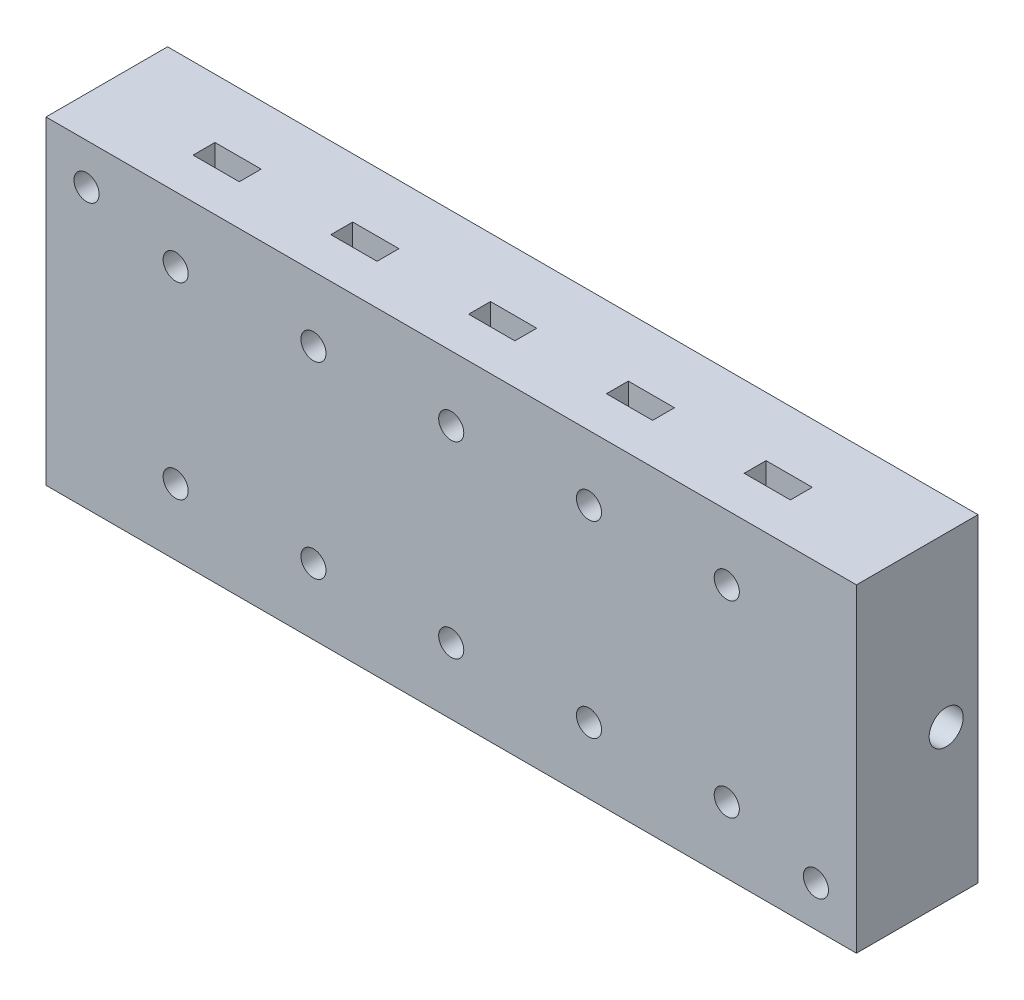
SolidWorks part; units mm, degrees
ref_plane "Ebene vorne" through (0, 0, 0) normal (0, 0, 1) x (1, 0, 0)
ref_plane "Ebene oben" through (0, 0, 0) normal (0, 1, 0) x (1, 0, 0)
ref_plane "Ebene rechts" through (0, 0, 0) normal (1, 0, 0) x (0, 0, -1)
sketch "Skizze2" plane through (0, 0, 0) normal (0, 0, 1) x (1, 0, 0)
  line L1 (0, 0) -> (100, 0)
  line L2 (0, 0) -> (0, 39.3642)
  line L3 (0, 39.3642) -> (100, 39.3642)
  line L4 (100, 0) -> (100, 39.3642)
  dimension "D1" = 39.3642
  dimension "D2" = 100
extrude "Aufsatz-Linear austragen1" add sketch "Skizze2" along normal blind 30
sketch "Skizze3" plane through (0, 0, 30) normal (0, 0, 1) x (1, 0, 0)
  line L0 (0, 19.6821) -> (100, 19.6821) construction
  line L1 (0, 39.3642) -> (0, 0) construction
  line L2 (100, 0) -> (100, 39.3642) construction
ref_plane "Ebene2" through (0, 19.7642, 0) normal (0, 1, 0) x (1, 0, 0)
sketch "Skizze9" plane through (0, 0, 30) normal (0, 0, 1) x (1, 0, 0)
  line L0 (50, 0) -> (50, 39.3642) construction
  line L1 (0, 0) -> (100, 0) construction
  line L2 (100, 39.3642) -> (0, 39.3642) construction
ref_plane "Ebene3" through (50, 0, 0) normal (-1, 0, 0) x (0, 0, 1)
sketch "Skizze10" plane through (50, 0, 0) normal (-1, 0, 0) x (0, 0, 1)
  line L0 (14.9458, 42.0451) -> (14.9458, -1.991) construction
  line L1 (-1.6741, 19.9497) -> (31.3778, 19.9497) construction
  circle A0 centre (14.9458, 20.027) radius 5
  dimension "D1" = 10
extrude "Schnitt-Linear austragen1" cut sketch "Skizze10" against normal blind 40 and the other way blind 40
ref_plane "Ebene4" through (90, 0, 0) normal (-1, 0, 0) x (0, 0, 1)
ref_plane "Ebene5" through (10, 0, 0) normal (-1, 0, 0) x (0, 0, 1)
sketch "Skizze17" plane through (90, 0, 0) normal (-1, 0, 0) x (0, 0, 1)
  circle A0 centre (14.9458, 20.027) radius 1.55
  dimension "D1" = 3.1
extrude "Schnitt-Linear austragen2" cut sketch "Skizze17" against normal blind 3
mirror "Spiegeln1" about plane through (50, 0, 0) normal (-1, 0, 0) of "Schnitt-Linear austragen2"
sketch "Skizze18" plane through (0, 39.3642, 0) normal (0, 1, 0) x (1, 0, 0)
  line L0 (100, -15) -> (0, -15) construction
  line L1 (100, -30) -> (100, 0) construction
ref_plane "Ebene6" through (0, 0, 15) normal (0, 0, -1) x (-1, 0, 0)
sketch "Skizze24" plane through (0, 0, 30) normal (0, 0, 1) x (1, 0, 0)
  line L0 (0, 39.3642) -> (0, 0) construction
  line L1 (100, 39.3642) -> (0, 39.3642) construction
  line L4 (100, 0) -> (100, 39.3642) construction
  circle A0 centre (16, 31.3642) radius 1.55
  circle A1 centre (33, 31.3642) radius 1.55
  circle A2 centre (50, 31.3642) radius 1.55
  circle A3 centre (67, 31.3642) radius 1.55
  circle A4 centre (84, 31.3642) radius 1.55
  dimension "D1" = 3.1
  dimension "D4" = 3.1
  dimension "D5" = 3.1
  dimension "D6" = 3.1
  dimension "D7" = 3.1
  dimension "D2" = 16
  dimension "D3" = 8
  dimension "D8" = 17
  dimension "D9" = 17
  dimension "D10" = 17
  dimension "D11" = 17
  dimension "D12" = 16
extrude "Schnitt-Linear austragen4" cut sketch "Skizze24" against normal through all
sketch "Skizze22" plane through (0, 0, 0) normal (-1, 0, 0) x (0, 0, 1)
  line L0 (30, 39.3642) -> (0, 39.3642) construction
  line L1 (0, 0) -> (15, 0)
  line L2 (0, 0) -> (0, 39.3642)
  line L3 (0, 39.3642) -> (15, 39.3642)
ref_plane "Ebene7" through (0, 0, 8.4) normal (0, 0, -1) x (-1, 0, 0)
ref_plane "Ebene8" through (16, 0, 0) normal (-1, 0, 0) x (0, 0, 1)
sketch "Skizze35" plane through (0, 0, 30) normal (0, 0, 1) x (1, 0, 0)
  line L0 (89.9018, 21.3451) -> (89.9018, 39.3769) construction
  line L1 (89.9018, 39.3769) -> (89.9018, 0) construction
  line L2 (0, 0) -> (100, 0) construction
ref_plane "Ebene9" through (90, 0, 0) normal (1, 0, 0) x (0, 0, -1)
sketch "Skizze36" plane through (90, 0, 0) normal (1, 0, 0) x (0, 0, -1)
  line L0 (-20.1004, 18.2046) -> (-18.9246, 18.6336)
  circle A0 centre (-18.9246, 18.6336) radius 0.75
  point P3 (-19.5125, 18.4191)
  dimension "D1" = 1.5
sketch "Skizze37" plane through (100, 0, 0) normal (1, 0, 0) x (0, 0, -1)
  circle A0 centre (-18.9246, 18.6336) radius 0.7369
extrude "Schnitt-Linear austragen9" cut sketch "Skizze37" against normal through all
sketch "Skizze40" plane through (100, 0, 0) normal (1, 0, 0) x (0, 0, -1)
  circle A0 centre (-18.9246, 18.6336) radius 2.1
  dimension "D1" = 4.2
extrude "Schnitt-Linear austragen10" cut sketch "Skizze40" against normal blind 6
sketch "Skizze42" plane through (0, 0, 0) normal (-1, 0, 0) x (0, 0, 1)
  line L0 (10.1439, 18.6336) -> (10.8642, 18.8426) construction
  circle A0 centre (14.9458, 20.027) radius 5 construction
  circle A1 centre (10.8642, 18.8426) radius 0.75
  dimension "D1" = 0.75
extrude "Schnitt-Linear austragen12" cut sketch "Skizze42" against normal blind 10
sketch "Skizze46" plane through (0, 0, 0) normal (0, 0, -1) x (-1, 0, 0)
  circle A0 centre (-84, 31.3642) radius 2.85
  dimension "D1" = 5.7
extrude "Schnitt-Linear austragen15" cut sketch "Skizze46" against normal blind 10
sketch "Skizze50" plane through (0, 0, 30) normal (0, 0, 1) x (1, 0, 0)
  line L0 (81.15, 33.0096) -> (81.15, 39.3642)
  line L2 (81.15, 33.0096) -> (81.15, 29.7187)
  line L3 (81.15, 29.7187) -> (84, 28.0733)
  line L4 (84, 28.0733) -> (86.85, 29.7187)
  line L5 (86.85, 29.7187) -> (86.85, 33.0096)
  line L7 (100, 39.3642) -> (0, 39.3642) construction
  line L8 (81.15, 39.3642) -> (86.85, 39.3642)
  line L9 (86.85, 39.3642) -> (86.85, 33.0096)
  line L11 (84, 34.6551) -> (81.15, 33.0096) [skipped]
  line L12 (86.85, 33.0096) -> (84, 34.6551) [skipped]
  circle A0 centre (84, 31.3642) radius 2.85 construction
  dimension "D1" = 5.7
extrude "Schnitt-Linear austragen25" cut sketch "Skizze50" against normal blind 2.7 from offset 5 offset against normal yes
pattern_linear "Lineares Muster1" count 5 spacing 17 along (-1, 0, 0) of "Schnitt-Linear austragen25", "Schnitt-Linear austragen15"
mirror "Spiegeln2" about plane through (0, 19.7642, 0) normal (0, 1, 0) of "Lineares Muster1", "Schnitt-Linear austragen15", "Schnitt-Linear austragen25"
mirror "Spiegeln3" about plane through (0, 19.7642, 0) normal (0, 1, 0) of "Schnitt-Linear austragen4"
sketch "Skizze51" plane through (0, 0, 30) normal (0, 0, 1) x (1, 0, 0)
  line L0 (100, 0) -> (100, 39.3642) construction
  line L1 (0, 0) -> (100, 0) construction
  line L2 (0, 0) -> (0, 39.3642) construction
  line L3 (100, 39.3642) -> (0, 39.3642) construction
  circle A0 centre (5, 34.3642) radius 1.55
  circle A1 centre (95, 5) radius 1.55
  dimension "D1" = 3.1
  dimension "D2" = 3.1
  dimension "D3" = 5
  dimension "D4" = 5
  dimension "D5" = 5
  dimension "D6" = 5
extrude "Schnitt-Linear austragen26" cut sketch "Skizze51" against normal through all
sketch "Skizze45" plane through (100, 0, 0) normal (1, 0, 0) x (0, 0, -1)
  line L1 (-15, 39.3642) -> (0, 39.3642)
  line L2 (-15, 39.3642) -> (-15, 0)
  line L3 (-15, 0) -> (0, 0)
  line L4 (0, 39.3642) -> (0, 0)
sketch "Skizze52" plane through (0, 0, 0) normal (-1, 0, 0) x (0, 0, 1)
  line L0 (30, 0) -> (30, 39.3642) construction
  line L1 (15, 0) -> (30, 0)
  line L2 (15, 0) -> (15, 39.3642)
  line L3 (15, 39.3642) -> (30, 39.3642)
  line L4 (30, 0) -> (30, 39.3642)
  line L5 (30, 39.3642) -> (0, 39.3642) construction
sketch "Skizze55" plane through (100, 0, 0) normal (1, 0, 0) x (0, 0, -1)
  line L0 (-15, 19.6821) -> (-12.6337, 21.0832) construction
  line L1 (-15, 39.3642) -> (-15, 0) construction
  circle A0 centre (-12.6337, 21.0832) radius 0.5
  point P5 (-12.6337, 21.0832)
  dimension "D2" = 1
  dimension "D1" = 2.75
extrude "Schnitt-Linear austragen28" cut sketch "Skizze55" against normal through all
sketch "Skizze57" plane through (100, 0, 0) normal (1, 0, 0) x (0, 0, -1)
  line L0 (-15, 0) -> (-15, 39.3642)
sketch "Skizze59" plane through (100, 0, 0) normal (1, 0, 0) x (0, 0, -1)
  circle A0 centre (-12.6337, 21.0832) radius 2.05
  dimension "D1" = 4.1
extrude "Schnitt-Linear austragen30" cut sketch "Skizze59" against normal blind 5
chamfer "Fase1" distance 1 angle 45 1 edges at (94, 18.6336, 18.1877)
chamfer "Fase2" distance 1 angle 45 1 edges at (95, 21.0832, 12.1337)
split "Abspalten3" trim tools "Skizze45" bodies to split 154 resulting bodies 155
